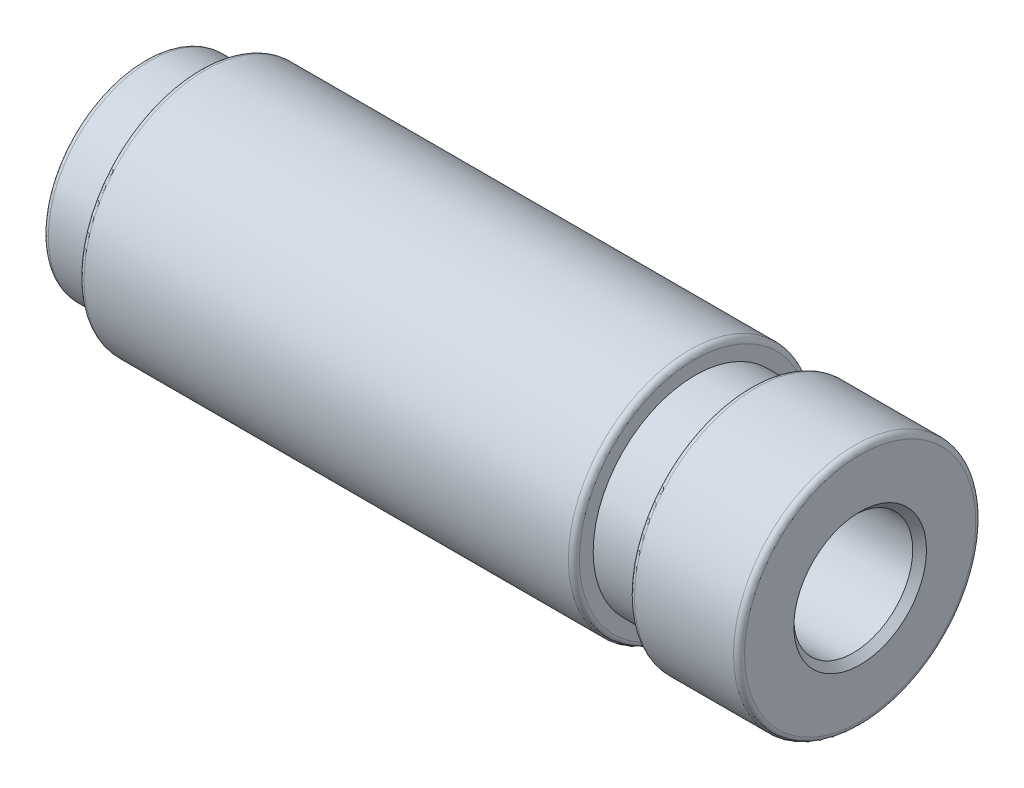
SolidWorks part; units mm, degrees
ref_plane "Plano frontal" through (0, 0, 0) normal (0, 0, 1) x (1, 0, 0)
ref_plane "Plano superior" through (0, 0, 0) normal (0, 1, 0) x (1, 0, 0)
ref_plane "Plano direito" through (0, 0, 0) normal (1, 0, 0) x (0, 0, -1)
sketch "Esboço1" plane through (0, 0, 0) normal (0, 0, 1) x (1, 0, 0)
  line L0 (0, 0) -> (65, 0)
  line L1 (65, 0) -> (65, 11)
  line L2 (65, 11) -> (55, 11)
  line L3 (55, 11) -> (55, 9.25)
  line L4 (55, 9.25) -> (50, 9.25)
  line L5 (50, 9.25) -> (50, 11)
  line L6 (50, 11) -> (5, 11)
  line L7 (5, 11) -> (5, 9.25)
  line L8 (5, 9.25) -> (0, 9.25)
  line L9 (0, 9.25) -> (0, 0)
  dimension "D1" = 5
  dimension "D2" = 10
  dimension "D3" = 5
  dimension "D4" = 65
  dimension "D5" = 1.75
  dimension "D6" = 1.75
  dimension "D7" = 11
  dimension "D8" = 11
revolve "Revolução1" add sketch "Esboço1" angle 360 about L0
cosmetic thread "Representação de rosca2" parameters "D1"=45, "D2"=6.619
sketch "Esboço2" plane through (0, 0, 0) normal (-1, 0, 0) x (0, 0, 1)
  circle A0 centre (0, 0) radius 4.8
  dimension "D1" = 9.6
extrude "Corte-extrusão1" cut sketch "Esboço2" against normal blind 33
hole_wizard "Furo roscado de M12x1.251" positions "Esboço3" profile "Esboço4" tap size "M12x1.25" standard "DIN"
sketch "Esboço3" plane through (65, 0, 0) normal (1, 0, 0) x (0, 0, -1)
  point P0 (0, 0)
sketch "Esboço4" plane through (65, 0, 0) normal (0, 1, 0) x (0, 0, -1)
  line L0 (0, 0) -> (0, 35.2446)
  line L1 (0, 35.2446) -> (5.4, 32)
  line L2 (5.4, 32) -> (5.4, 0.625)
  line L3 (5.4, 0.625) -> (6.025, 0)
  line L5 (6.025, 0) -> (0, 0)
  line L6 (-5.4, 0.625) -> (-6.025, 0) construction
  line L10 (0, 35.2446) -> (-5.4, 32) construction
  line L11 (0, -6.35) -> (0, 107.95) construction
  dimension "Tap Drill Dia." = 10.8
  dimension "Tap Drill Depth" = 32
  dimension "Near C'Sink Dia." = 12.05
  dimension "Near C'Sink Angle" = 90
  dimension "Drill Angle" = 118
cosmetic thread "Rosca de furo1" parameters "D1"=32, "D2"=12
fillet "Filete1" radius 1.5 1 edges at (0, 0, 4.8)
fillet "Filete2" radius 0.5 1 edges at (0, 0, 9.25)
fillet "Filete3" radius 0.5 3 edges at (65, 0, 11) (55, 0, 11) (50, 0, 11)
fillet "Filete4" radius 0.5 1 edges at (5, 0, 11)
